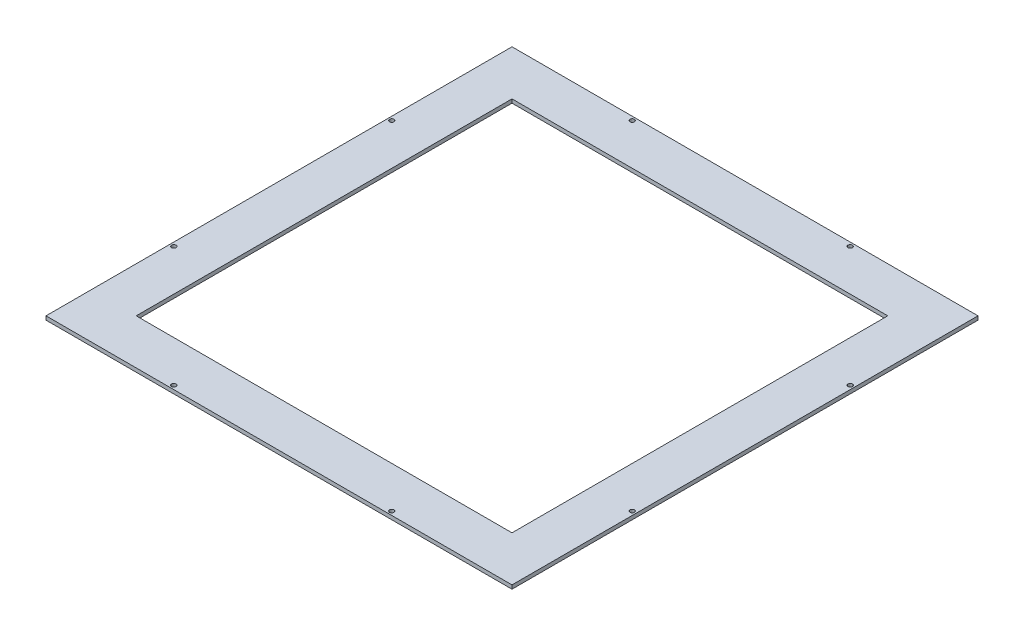
SolidWorks part; units mm, degrees
ref_plane "Front Plane" through (0, 0, 0) normal (0, 0, 1) x (1, 0, 0)
ref_plane "Top Plane" through (0, 0, 0) normal (0, 1, 0) x (1, 0, 0)
ref_plane "Right Plane" through (0, 0, 0) normal (1, 0, 0) x (0, 0, -1)
sketch "Sketch1" plane through (0, 0, 0) normal (0, 1, 0) x (1, 0, 0)
  line L1 (-196.85, 196.85) -> (196.85, 196.85)
  line L2 (-196.85, 196.85) -> (-196.85, -196.85)
  line L3 (-196.85, -196.85) -> (196.85, -196.85)
  line L4 (196.85, 196.85) -> (196.85, -196.85)
  line L5 (-196.85, 196.85) -> (196.85, -196.85) construction
  line L6 (-196.85, -196.85) -> (196.85, 196.85) construction
  point P0 (0, 0)
extrude "Boss-Extrude1" add sketch "Sketch1" along normal blind 3.175
sketch "Sketch2" plane through (0, 3.175, 0) normal (0, 1, 0) x (1, 0, 0)
  line L1 (-158.75, -158.75) -> (158.75, -158.75)
  line L2 (-158.75, -158.75) -> (-158.75, 158.75)
  line L3 (-158.75, 158.75) -> (158.75, 158.75)
  line L4 (158.75, -158.75) -> (158.75, 158.75)
  line L5 (-158.75, -158.75) -> (158.75, 158.75) construction
  line L6 (-158.75, 158.75) -> (158.75, -158.75) construction
  point P0 (0, 0)
extrude "Cut-Extrude1" cut sketch "Sketch2" against normal through all
sketch "Sketch3" plane through (0, 3.175, 0) normal (0, 1, 0) x (1, 0, 0)
  line L0 (-196.85, -196.85) -> (196.85, -196.85) construction
  line L1 (196.85, -196.85) -> (196.85, 196.85) construction
  line L2 (196.85, 196.85) -> (-196.85, 196.85) construction
  line L3 (-196.85, 196.85) -> (-196.85, -196.85) construction
  circle A0 centre (-92.075, -193.675) radius 1.905
  circle A1 centre (92.075, -193.675) radius 1.905
  circle A2 centre (193.675, -92.075) radius 1.905
  circle A3 centre (193.675, 92.075) radius 1.905
  circle A4 centre (92.075, 193.675) radius 1.905
  circle A5 centre (-92.075, 193.675) radius 1.905
  circle A6 centre (-193.675, 92.075) radius 1.905
  circle A7 centre (-193.675, -92.075) radius 1.905
  dimension "D1" = 3.175
  dimension "D2" = 3.175
  dimension "D3" = 3.175
  dimension "D4" = 3.175
  dimension "D5" = 3.175
  dimension "D6" = 3.175
  dimension "D7" = 3.175
  dimension "D8" = 104.775
  dimension "D9" = 184.15
  dimension "D10" = 104.775
  dimension "D11" = 184.15
  dimension "D12" = 104.775
  dimension "D13" = 184.15
  dimension "D14" = 104.775
  dimension "D15" = 184.15
  dimension "D16" = 3.175
extrude "Cut-Extrude3" cut sketch "Sketch3" against normal through all
